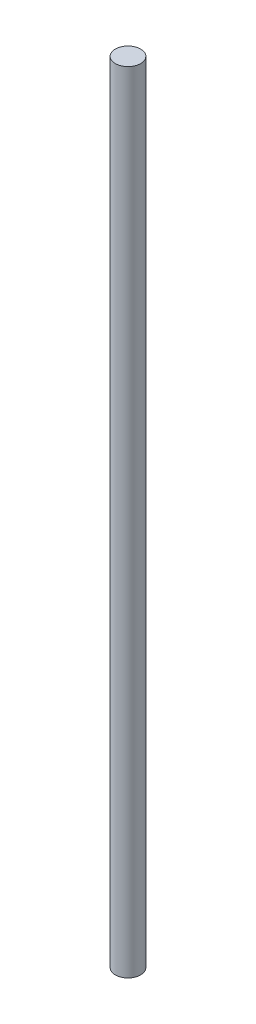
SolidWorks part; units mm, degrees
ref_plane "Front Plane" through (0, 0, 0) normal (0, 0, 1) x (1, 0, 0)
ref_plane "Top Plane" through (0, 0, 0) normal (0, 1, 0) x (1, 0, 0)
ref_plane "Right Plane" through (0, 0, 0) normal (1, 0, 0) x (0, 0, -1)
sketch "Sketch1" plane through (0, 0, 0) normal (0, 1, 0) x (1, 0, 0)
  circle A0 centre (0, 0) radius 4
  dimension "D1" = 8
extrude "Boss-Extrude1" add sketch "Sketch1" along normal blind 250
